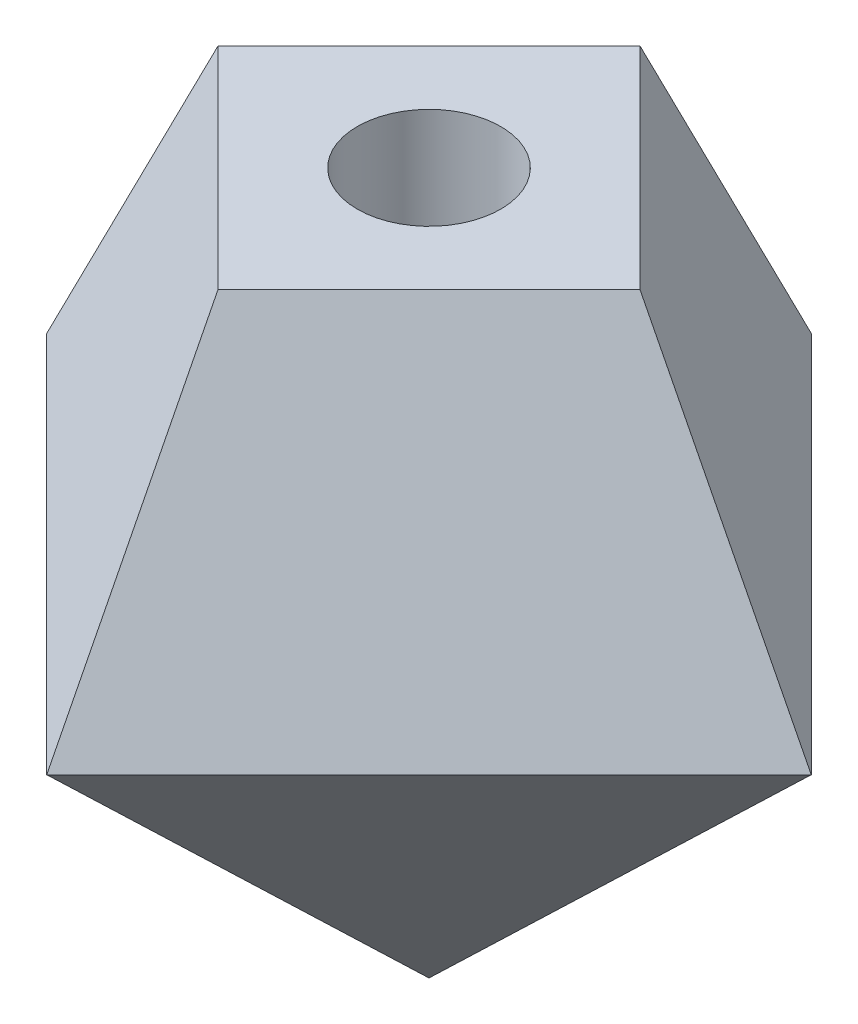
SolidWorks part; units mm, degrees
ref_plane "Front Plane" through (0, 0, 0) normal (0, 0, 1) x (1, 0, 0)
ref_plane "Top Plane" through (0, 0, 0) normal (0, 1, 0) x (1, 0, 0)
ref_plane "Right Plane" through (0, 0, 0) normal (1, 0, 0) x (0, 0, -1)
sketch "Sketch1" plane through (0, 0, 0) normal (0, 0, 1) x (1, 0, 0)
  line L0 (64.8756, 27.2935) -> (90.2756, 27.2935)
  line L1 (90.2756, 27.2935) -> (90.2756, 49.5185)
  line L2 (90.2756, 49.5185) -> (76.2538, 49.5185)
  line L3 (76.2538, 49.5185) -> (64.8756, 27.2935)
  dimension "D1" = 25.4
  dimension "D2" = 22.225
extrude "Boss-Extrude1" add sketch "Sketch1" along normal blind 25.4
ref_plane "Plane1" through (22.5024, -11.5202, -22.5024) normal (-0.6649, 0.3404, 0.6649) x (0.7469, 0.303, 0.5918)
sketch "Sketch2" plane through (22.5024, -11.5202, -22.5024) normal (-0.6649, 0.3404, 0.6649) x (0.7469, 0.303, 0.5918)
  line L1 (49.6267, 57.9633) -> (98.4694, 57.9633)
  line L2 (49.6267, 57.9633) -> (49.6267, 0)
  line L3 (49.6267, 0) -> (98.4694, 0)
  line L4 (98.4694, 57.9633) -> (98.4694, 0)
extrude "Cut-Extrude1" cut sketch "Sketch2" along normal blind 25.4
pattern_circular "CirPattern1" count 4 over 360 about axis through (90.2756, 0, 0) along (0, 1, 0) of "Boss-Extrude1", "Cut-Extrude1"
sketch "Sketch3" plane through (0, 0, 0) normal (0, 0, 1) x (1, 0, 0)
  line L0 (90.2756, 27.2935) -> (64.8756, 27.2935)
  line L1 (64.8756, 27.2935) -> (90.2756, 2.898)
  line L2 (90.2756, 2.898) -> (90.2756, 27.2935)
extrude "Boss-Extrude2" add sketch "Sketch3" along normal blind 25.4
ref_plane "Plane2" through (30.2502, 31.4957, -30.2502) normal (0.5694, 0.5929, -0.5694) x (0.822, -0.4107, 0.3944)
sketch "Sketch4" plane through (30.2502, 31.4957, -30.2502) normal (0.5694, 0.5929, -0.5694) x (0.822, -0.4107, 0.3944)
  line L1 (93.4914, -1.5905) -> (37.9797, -1.5905)
  line L2 (93.4914, -1.5905) -> (93.4914, -39.0528)
  line L3 (93.4914, -39.0528) -> (37.9797, -39.0528)
  line L4 (37.9797, -1.5905) -> (37.9797, -39.0528)
extrude "Cut-Extrude2" cut sketch "Sketch4" against normal blind 25.4
pattern_circular "CirPattern2" count 4 over 360 about axis through (90.2756, 0, 0) along (0, 1, 0) of "Boss-Extrude2", "Cut-Extrude2"
sketch "Sketch5" plane through (0, 49.5185, 0) normal (0, 1, 0) x (1, 0, 0)
  circle A0 centre (90.2756, 0) radius 4.7625
  dimension "D1" = 9.525
extrude "Cut-Extrude3" cut sketch "Sketch5" against normal blind 25.4
